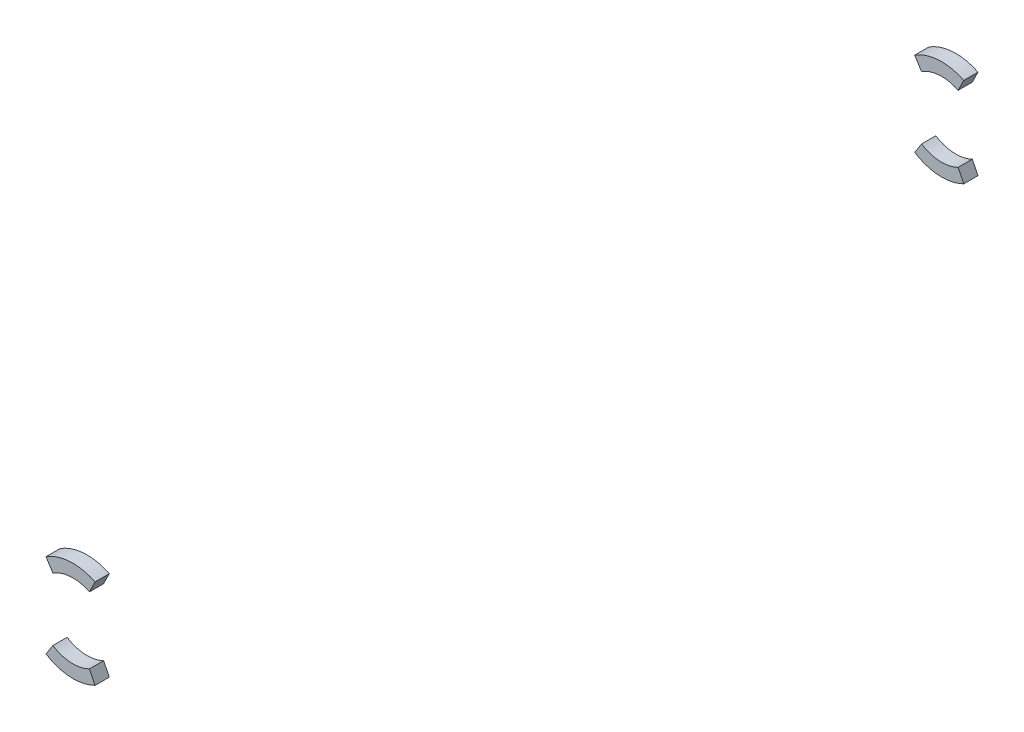
SolidWorks part; units mm, degrees
material "1023 Carbon Steel Sheet (SS)"
ref_plane "Front Plane" through (0, 0, 0) normal (0, 0, 1) x (1, 0, 0)
ref_plane "Top Plane" through (0, 0, 0) normal (0, 1, 0) x (1, 0, 0)
ref_plane "Right Plane" through (0, 0, 0) normal (1, 0, 0) x (0, 0, -1)
sketch "Sketch1" plane through (0, 0, 0) normal (0, 0, 1) x (1, 0, 0)
  circle A0 centre (0, 0) radius 90
  dimension "D1" = 180
extrude "Boss-Extrude1" [suppressed] add sketch "Sketch1" along normal blind 1200
sketch "Sketch2" plane through (0, 0, 0) normal (0, 0, 1) x (1, 0, 0)
  line L0 (-37.8215, 59.139) -> (0, 0) construction
  line L1 (0, 0) -> (31.1075, 62.9302) construction
  line L2 (-37.8215, 59.139) -> (-28.1601, 44.0322)
  line L3 (31.1075, 62.9302) -> (23.1612, 46.8549)
  line L4 (0, 0) -> (144.0107, 0) construction
  line L5 (31.1075, -62.9302) -> (23.1612, -46.8549)
  line L6 (-37.8215, -59.139) -> (-28.1601, -44.0322)
  arc A0 (-37.8215, 59.139) -> (31.1075, 62.9302) centre (0, 0) cw
  arc A1 (-28.1601, 44.0322) -> (23.1612, 46.8549) centre (0, 0) cw
  arc A2 (-37.8215, -59.139) -> (31.1075, -62.9302) centre (0, 0) ccw
  arc A3 (-28.1601, -44.0322) -> (23.1612, -46.8549) centre (0, 0) ccw
extrude "Boss-Extrude2" add sketch "Sketch2" against normal blind 20 separate body
pattern_linear "LPattern1" count 2 spacing 1220 along (0, 0, 1) of "Boss-Extrude2"
